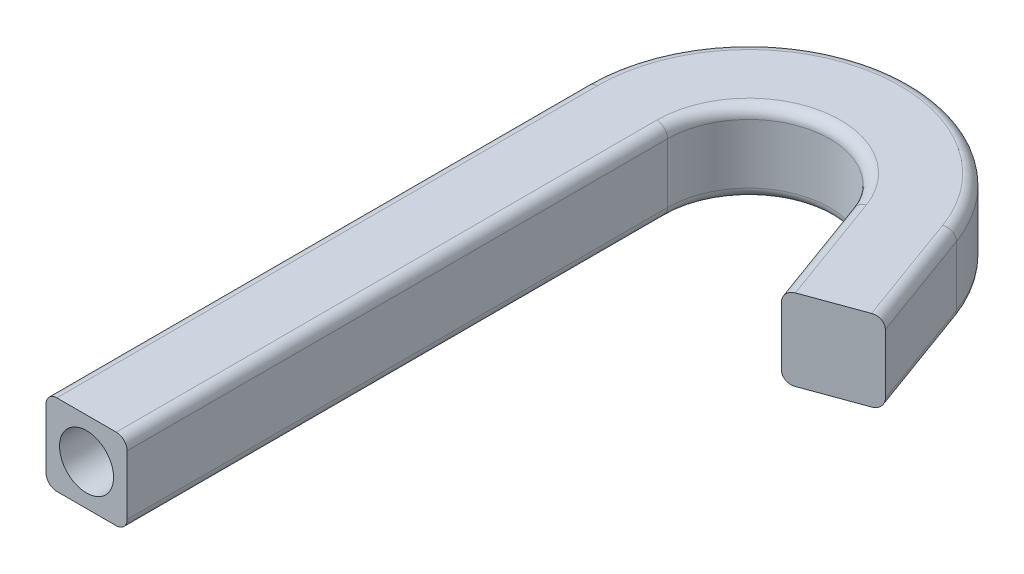
SolidWorks part; units mm, degrees
ref_plane "Front Plane" through (0, 0, 0) normal (0, 0, 1) x (1, 0, 0)
ref_plane "Top Plane" through (0, 0, 0) normal (0, 1, 0) x (1, 0, 0)
ref_plane "Right Plane" through (0, 0, 0) normal (1, 0, 0) x (0, 0, -1)
sketch "Sketch1" plane through (0, 0, 0) normal (0, 1, 0) x (1, 0, 0)
  line L0 (27.4623, -19.7535) -> (45.3634, -13.2381)
  line L2 (-38.1, 0) -> (-38.1, -127)
  line L3 (-38.1, -127) -> (-19.05, -127)
  line L4 (-19.05, 0) -> (-19.05, -127)
  line L6 (17.9011, 6.5155) -> (27.4623, -19.7535)
  line L7 (35.8023, 13.031) -> (45.3634, -13.2381)
  arc A0 (17.9011, 6.5155) -> (-19.05, 0) centre (0, 0) ccw
  arc A2 (35.8023, 13.031) -> (-38.1, 0) centre (0, 0) ccw
  dimension "D1" = 38.1
  dimension "D2" = 127
extrude "Boss-Extrude1" add sketch "Sketch1" along normal blind 19.05
sketch "Sketch9" plane through (0, 0, 127) normal (0, 0, 1) x (1, 0, 0)
  circle A0 centre (-28.575, 9.525) radius 6.35
  dimension "D1" = 12.7
extrude "Cut-Extrude2" cut sketch "Sketch9" against normal blind 34.29
fillet "Fillet1" radius 2.54 12 edges at (22.6817, 19.05, 6.619) (-3.308, 19.05, -18.7606) (22.6817, 0, 6.619) (-3.308, 0, -18.7606) (-19.05, 0, 63.5) (-19.05, 19.05, 63.5) (-38.1, 0, 63.5) (-6.616, 0, -37.5212) (40.5829, 0, 0.1035) (40.5829, 19.05, 0.1035) (-6.616, 19.05, -37.5212) (-38.1, 19.05, 63.5)
